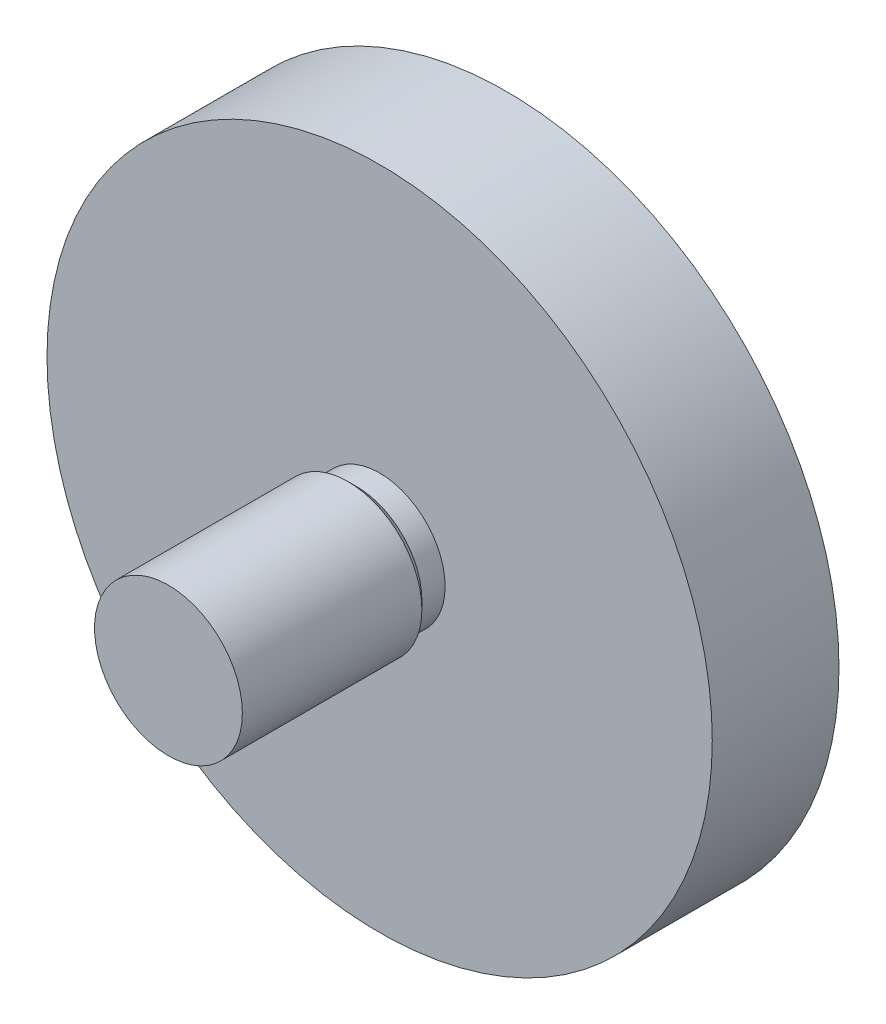
SolidWorks part; units mm, degrees
material "1.0553 (S355J0)"
ref_plane "XY Plane" through (0, 0, 0) normal (0, 0, 1) x (1, 0, 0)
ref_plane "XZ Plane" through (0, 0, 0) normal (0, 1, 0) x (1, 0, 0)
ref_plane "YZ Plane" through (0, 0, 0) normal (1, 0, 0) x (0, 0, -1)
sketch "Sketch1" plane through (0, 0, 0) normal (1, 0, 0) x (0, 0, -1)
  line L0 (8, 0) -> (8, 6)
  line L1 (8, 6) -> (0, 6)
  line L2 (0, 6) -> (0, 31.5)
  line L3 (0, 31.5) -> (-12, 31.5)
  line L4 (-12, 31.5) -> (-12, 6.2)
  line L5 (-12, 6.2) -> (-14.2, 6.2)
  line L6 (-14.2, 6.2) -> (-15, 7)
  line L7 (-15, 7) -> (-32, 7)
  line L8 (-32, 7) -> (-32, 0)
  line L9 (-32, 0) -> (8, 0)
  line L10 (8, 0) -> (117.2164, 0) construction
  line L11 (0, 0) -> (0, 6) construction
  dimension "D1" = 45
  dimension "Ulkohalkaisija" = 63
  dimension "D3" = 12
  dimension "TapinHalkaisija" = 14
  dimension "D6" = 8
  dimension "D7" = 3
  dimension "LaipanPaksuus" = 12
  dimension "D9" = 0.8
  dimension "Kokonaispituus" = 40
revolve "Revolve1" add sketch "Sketch1" angle 360 about L10
